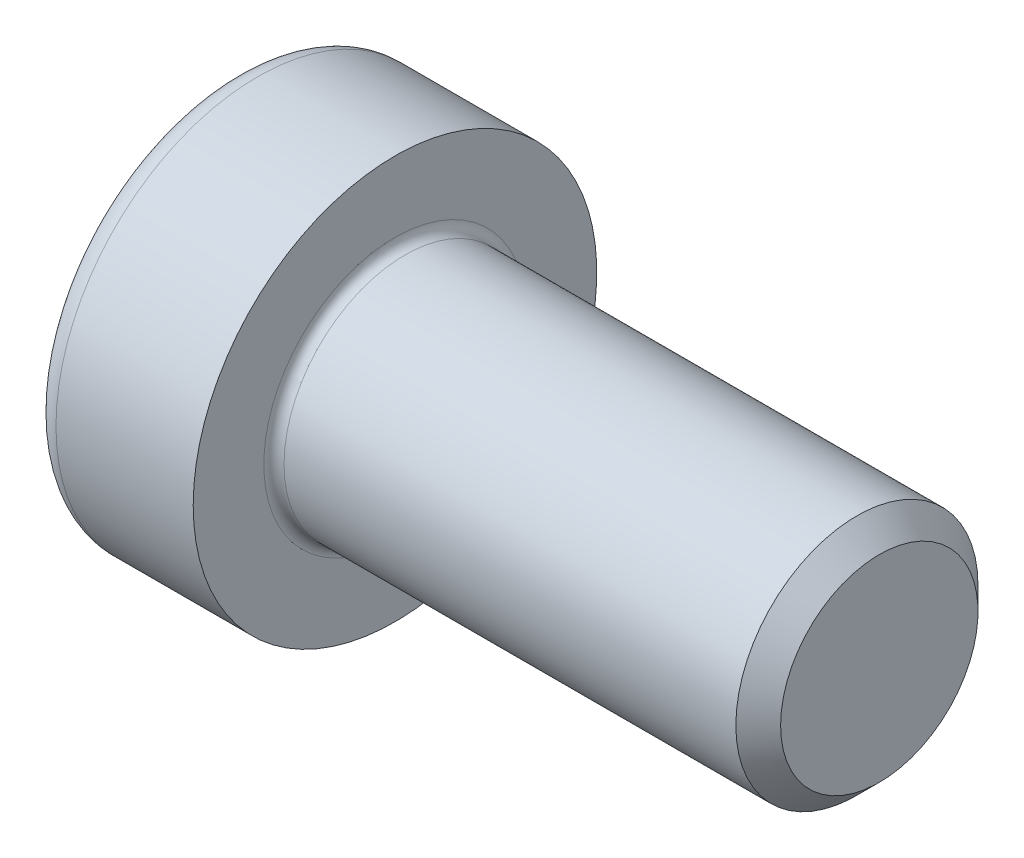
SolidWorks part; units mm, degrees
revolve "Base-Revolve" add sketch "BodySke"
sketch "BodySke" plane through (0, 0, 0) normal (0, 0, 1) x (1, 0, 0)
  line L0 (0, 0) -> (0, 5)
  line L1 (0, 5) -> (4, 5)
  line L2 (4, 5) -> (4, 3)
  line L3 (4, 3) -> (15.4455, 3)
  line L4 (16, 2.4455) -> (16, 0)
  line L5 (16, 0) -> (0, 0)
  line L6 (-31.75, 0) -> (127, 0) construction
  line L8 (16, 2.4455) -> (15.4455, 3)
  line L10 (16, -2.4455) -> (15.4455, -3) construction
  line L11 (5, 4.525) -> (5, -1.825) construction
  line L12 (4, 4.525) -> (4, -1.825) construction
  line L13 (-44, 4.525) -> (-44, -1.825) construction
  dimension "Head_ht" = 4
  dimension "Length" = 12
  dimension "Body_ch_ang" = 45
  dimension "Diameter" = 6
  dimension "Minor_dia" = 4.891
  dimension "Advance" = 1
  dimension "Thread_nom" = 12
  dimension "Thread_length" = 60
  dimension "Head_dia" = 10
cosmetic thread "ThreadCosmetic"
fillet "Fillet1" radius 0.25 1 edges at (4, 0, 3)
fillet "Fillet2" radius 0.6 1 edges at (0, 0, 5)
ref_plane "Plane1" through (0, 0, 0) normal (0, 0, 1) x (1, 0, 0)
ref_plane "Plane2" through (0, 0, 0) normal (0, 1, 0) x (1, 0, 0)
ref_plane "Plane3" through (0, 0, 0) normal (1, 0, 0) x (0, 0, -1)
sketch "HexSke" plane through (0, 0, 0) normal (-1, 0, 0) x (0, 0.5, 0.866)
  line L0 (1.4434, 2.5) -> (-1.4434, 2.5)
  line L1 (-1.4434, 2.5) -> (-2.8868, 0)
  line L2 (1.4434, 2.5) -> (2.8868, 0)
  line L3 (1.4434, -2.5) -> (2.8868, 0)
  line L4 (1.4434, -2.5) -> (-1.4434, -2.5)
  line L5 (-1.4434, -2.5) -> (-2.8868, 0)
  dimension "D1" = 2.5
  dimension "D2" = 2.5
  dimension "Hex_size" = 5
extrude "Hex" cut sketch "HexSke" against normal blind 2.5
sketch "PilotSke" plane through (0, 0, 0) normal (0, 0, 1) x (1, 0, 0)
  line L0 (0, 2.5) -> (2.5, 2.5)
  line L1 (2.5, 2.5) -> (3.0774, 1.5)
  line L2 (-31.75, 0) -> (127, 0) construction
  line L3 (5.866, 0) -> (0, 0)
  line L4 (0, 0) -> (0, 2.5)
  line L5 (3.0774, 1.5) -> (5, 1.5)
  line L6 (0, 0) -> (47.625, 0) construction
  line L7 (5, 1.5) -> (5.866, 0)
  dimension "D1" = 2.5
  dimension "D2" = 60
  dimension "Depth" = 2.5
  dimension "Pilot_dia" = 3
  dimension "Pilot_Depth" = 5
revolve "Hex-PreBroach" cut sketch "PilotSke" angle 360 about L6
sketch "ThdSchSke" plane through (0, 0, 0) normal (0, 0, 1) x (1, 0, 0)
  line L0 (7, -2.4455) -> (6.6117, -3)
  line L1 (7, -2.4455) -> (7.3883, -3)
  line L2 (7.3883, -3) -> (7.3883, -3.75)
  line L3 (-3.175, 0) -> (5.1513, 0) construction
  line L4 (0, 4.4) -> (0, -4.4) construction
  line L5 (7.3883, -3.75) -> (6.6117, -3.75)
  line L6 (6.6117, -3.75) -> (6.6117, -3)
  dimension "Thread_minor" = 4.891
  dimension "Diameter" = 6
  dimension "Start" = 7
revolve "ThreadSchematic" [suppressed] cut sketch "ThdSchSke" angle 360 about L3
pattern_linear "ThdSchPat" [suppressed]
equation "\"D2@HexSke\" = \"Hex_size@HexSke\" / 2"
equation "\"D1@HexSke\" = \"Hex_size@HexSke\" / 2"
equation "\"D1@PilotSke\" = \"Hex_size@HexSke\" / 2"
equation "\"Thread_minor@ThreadCosmetic\"  =  \"Minor_dia@BodySke\""
equation "\"Depth@PilotSke\" =  \"Key_eng@Hex\""
equation "\"Thread_length@ThreadCosmetic\" = ((sgn( (\"Length@BodySke\" - \"Advance@BodySke\" * 3.0) - \"Thread_nom@BodySke\" )-1)*( (\"Length@BodySke\" - \"Advance@BodySke\" * 3.0) - \"Thread_nom@BodySke\" ))/-2+ \"Thread_nom@BodySke\""
equation "\"Thread_minor@ThdSchSke\" = \"Minor_dia@BodySke\""
equation "\"Diameter@ThdSchSke\" = \"Diameter@BodySke\""
equation "\"Overcut@ThdSchSke\" = \"Diameter@BodySke\" * 1.25"
equation "\"Start@ThdSchSke\" = \"Head_ht@BodySke\" + \"Length@BodySke\" - \"Thread_length@ThreadCosmetic\"  '---Non-countersunk---"
equation "\"Num_threads@ThdSchPat\" = int( \"Thread_length@ThreadCosmetic\" / \"Advance@BodySke\" + 0.999 )  + 1"
equation "\"Advance@ThdSchPat\" = \"Thread_length@ThreadCosmetic\" /  (\"Num_threads@ThdSchPat\" - 1) 'relax it"
equation "\"Num_threads@ThdSchPat\" = \"Num_threads@ThdSchPat\" - sgn( \"Num_threads@ThdSchPat\" - 1) '---chamfered tips only---"
